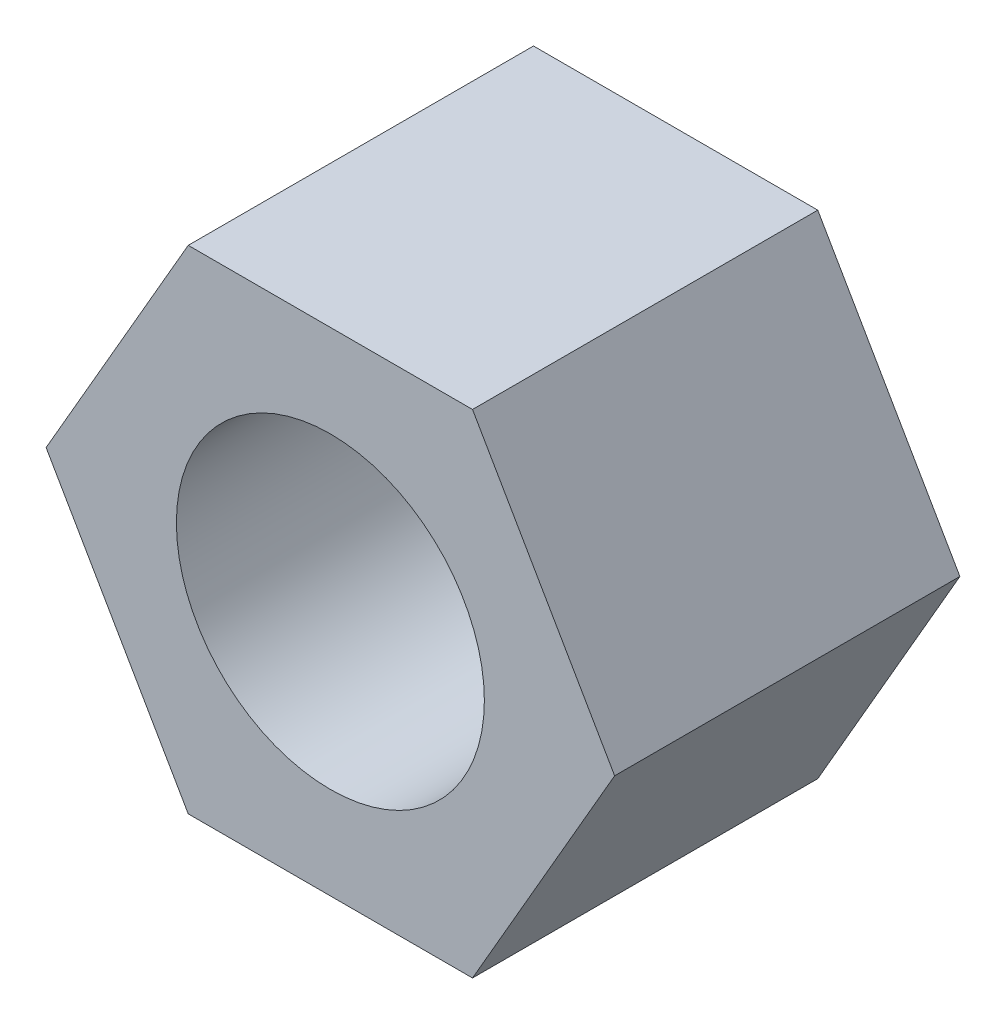
SolidWorks part; units mm, degrees
ref_plane "Front Plane" through (0, 0, 0) normal (0, 0, 1) x (1, 0, 0)
ref_plane "Top Plane" through (0, 0, 0) normal (0, 1, 0) x (1, 0, 0)
ref_plane "Right Plane" through (0, 0, 0) normal (1, 0, 0) x (0, 0, -1)
sketch "Sketch1" plane through (0, 0, 0) normal (0, 0, 1) x (1, 0, 0)
  line L1 (3.6229, -6.275) -> (7.2457, 0)
  line L2 (7.2457, 0) -> (3.6229, 6.275)
  line L3 (3.6229, 6.275) -> (-3.6229, 6.275)
  line L4 (-3.6229, 6.275) -> (-7.2457, 0)
  line L5 (-7.2457, 0) -> (-3.6229, -6.275)
  line L6 (-3.6229, -6.275) -> (3.6229, -6.275)
  circle A0 centre (0, 0) radius 6.275 construction
  circle A1 centre (0, 0) radius 3.925
  dimension "D2" = 7.85
  dimension "D1" = 12.55
extrude "Boss-Extrude1" add sketch "Sketch1" along normal blind 8.8
